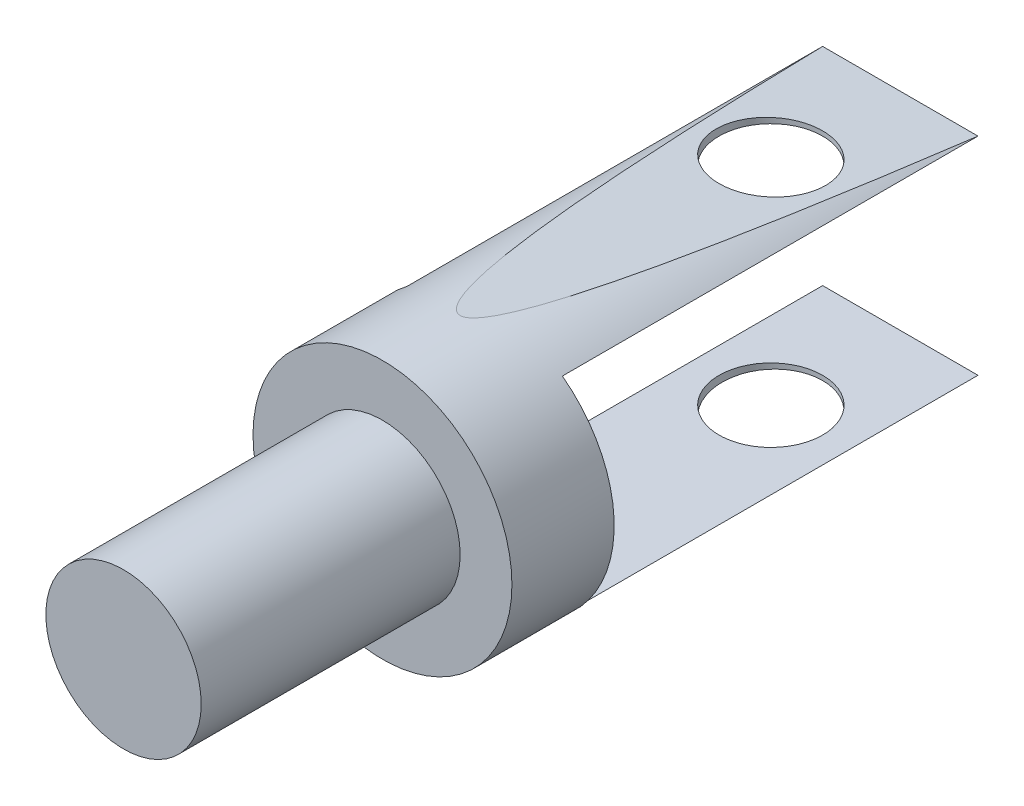
SolidWorks part; units mm, degrees
ref_plane "Front Plane" through (0, 0, 0) normal (0, 0, 1) x (1, 0, 0)
ref_plane "Top Plane" through (0, 0, 0) normal (0, 1, 0) x (1, 0, 0)
ref_plane "Right Plane" through (0, 0, 0) normal (1, 0, 0) x (0, 0, -1)
sketch "Sketch1" plane through (0, 0, 0) normal (0, 0, 1) x (1, 0, 0)
  circle A0 centre (0, 0) radius 5
  dimension "D1" = 10
extrude "Boss-Extrude1" add sketch "Sketch1" along normal blind 20
sketch "Sketch2" plane through (0, 0, 20) normal (0, 0, 1) x (1, 0, 0)
  circle A0 centre (0, 0) radius 3
  dimension "D1" = 6
extrude "Boss-Extrude2" add sketch "Sketch2" along normal blind 10
sketch "Sketch3" plane through (0, 0, 0) normal (1, 0, 0) x (0, 0, -1)
  line L0 (0, 5) -> (-17, 5)
  line L1 (0, 5) -> (-20, 5) construction
  line L2 (-17, 5) -> (0, 4)
  line L3 (0, -5) -> (0, 5) construction
  line L4 (0, 4) -> (0, 5)
  line L5 (-17, -5) -> (0, -5)
  line L6 (0, -5) -> (0, -4)
  line L7 (0, -4) -> (-17, -5)
  dimension "D1" = 1
  dimension "D2" = 1
  dimension "D3" = 17
  dimension "D4" = 17
extrude "Cut-Extrude1" cut sketch "Sketch3" against normal mid plane 10
sketch "Sketch4" plane through (0, 0, 0) normal (1, 0, 0) x (0, 0, -1)
  line L0 (0, 4) -> (-16.0513, 4)
  line L1 (0, -4) -> (0, 4) construction
  line L2 (-16.0513, 4) -> (-16.0513, -4)
  line L3 (-16.0513, -4) -> (0, -4)
  line L4 (0, -4) -> (0, 4)
  dimension "D1" = 8
extrude "Cut-Extrude2" cut sketch "Sketch4" against normal mid plane 10
sketch "Sketch5" plane through (0, 0, 0) normal (0, 1, 0) x (1, 0, 0)
  circle A0 centre (0, -5) radius 2
  dimension "D1" = 4
  dimension "D2" = 5
extrude "Cut-Extrude3" cut sketch "Sketch5" against normal mid plane 10
